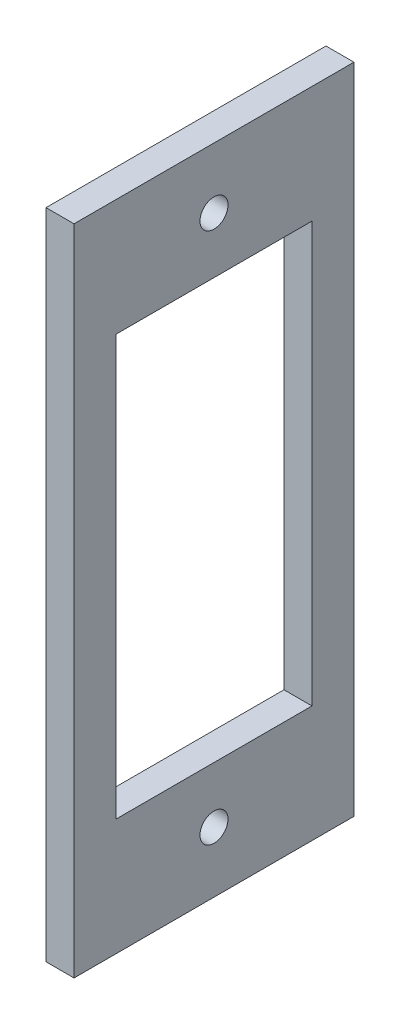
SolidWorks part; units mm, degrees
ref_plane "Front Plane" through (0, 0, 0) normal (0, 0, 1) x (1, 0, 0)
ref_plane "Top Plane" through (0, 0, 0) normal (0, 1, 0) x (1, 0, 0)
ref_plane "Right Plane" through (0, 0, 0) normal (1, 0, 0) x (0, 0, -1)
sketch "Sketch1" plane through (0, 0, 0) normal (1, 0, 0) x (0, 0, -1)
  line L1 (15, -35) -> (-15, -35)
  line L2 (15, -35) -> (15, 35)
  line L3 (15, 35) -> (-15, 35)
  line L4 (-15, -35) -> (-15, 35)
  line L5 (15, -35) -> (-15, 35) construction
  line L6 (15, 35) -> (-15, -35) construction
  point P0 (0, 0)
  dimension "D1" = 30
  dimension "D2" = 70
extrude "Boss-Extrude1" add sketch "Sketch1" along normal blind 3
sketch "Sketch2" plane through (3, 0, 0) normal (1, 0, 0) x (0, 0, -1)
  line L0 (0, 0) -> (15, 0) construction
  line L1 (10.5, -22.5) -> (-10.5, -22.5)
  line L2 (10.5, -22.5) -> (10.5, 22.5)
  line L3 (10.5, 22.5) -> (-10.5, 22.5)
  line L4 (-10.5, -22.5) -> (-10.5, 22.5)
  line L5 (10.5, -22.5) -> (-10.5, 22.5) construction
  line L6 (10.5, 22.5) -> (-10.5, -22.5) construction
  line L7 (15, -35) -> (15, 35) construction
  line L8 (0, 0) -> (0, 35) construction
  line L9 (15, 35) -> (-15, 35) construction
  line L10 (-15, -35) -> (15, -35) construction
  circle A0 centre (0, 28.5) radius 1.5
  circle A1 centre (0, -28.5) radius 1.5
  point P0 (0, 0)
  point P17 (0, -35)
  dimension "D3" = 3
  dimension "D5" = 15
  dimension "D1" = 45
  dimension "D2" = 21
  dimension "D4" = 6
extrude "Cut-Extrude1" cut sketch "Sketch2" against normal through all
